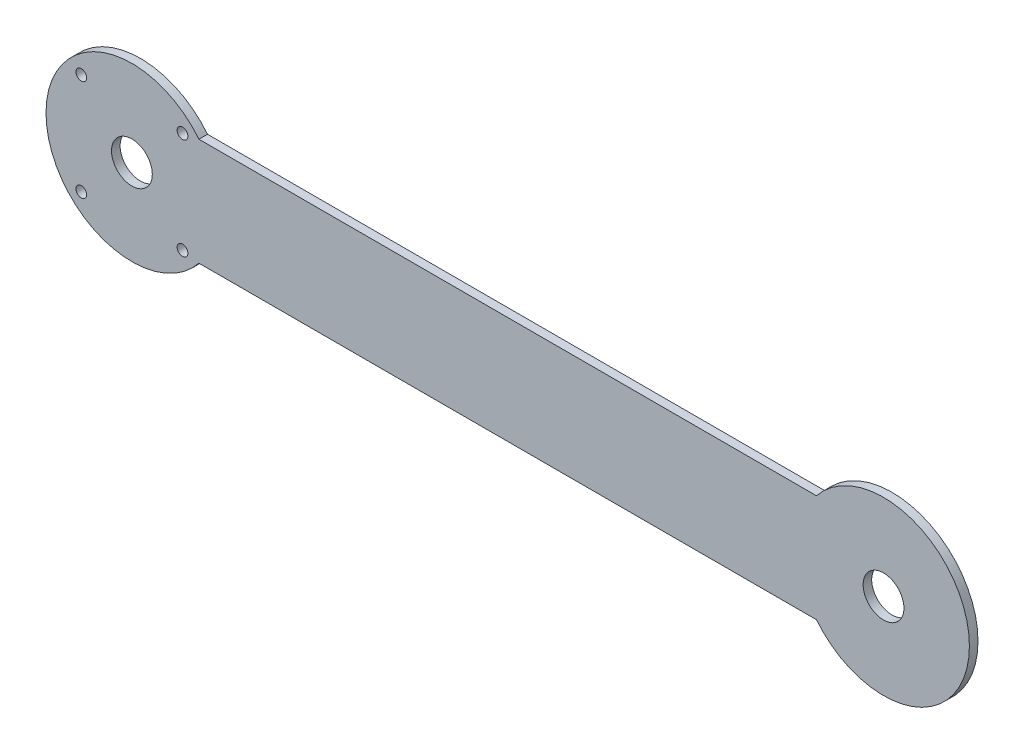
SolidWorks part; units mm, degrees
ref_plane "前视基准面" through (0, 0, 0) normal (0, 0, 1) x (1, 0, 0)
ref_plane "上视基准面" through (0, 0, 0) normal (0, 1, 0) x (1, 0, 0)
ref_plane "右视基准面" through (0, 0, 0) normal (1, 0, 0) x (0, 0, -1)
sketch "草图1" plane through (0, 0, 0) normal (0, 0, 1) x (1, 0, 0)
  line L0 (0, 0) -> (350, 0) construction
  line L1 (31.225, 25) -> (318.775, 25)
  line L2 (31.225, -25) -> (318.775, -25)
  circle A0 centre (-23.57, 23.57) radius 2.5
  circle A1 centre (23.57, 23.57) radius 2.5
  circle A2 centre (23.57, -23.57) radius 2.5
  circle A3 centre (-23.57, -23.57) radius 2.5
  circle A4 centre (0, 0) radius 40 construction
  circle A5 centre (350, 0) radius 40 construction
  arc A6 (31.225, 25) -> (31.225, -25) centre (0, 0) ccw
  arc A7 (318.775, 25) -> (318.775, -25) centre (350, 0) cw
  circle A8 centre (350, 0) radius 9.5
  circle A9 centre (0, 0) radius 9.5
  dimension "D1" = 5
  dimension "D5" = 80
  dimension "D7" = 19
  dimension "D8" = 19
  dimension "D2" = 23.57
  dimension "D3" = 23.57
  dimension "D6" = 25
  dimension "D9" = 350
  dimension "D4" = 4
extrude "凸台-拉伸1" add sketch "草图1" along normal blind 4 contours L2 A7 L1 A6
